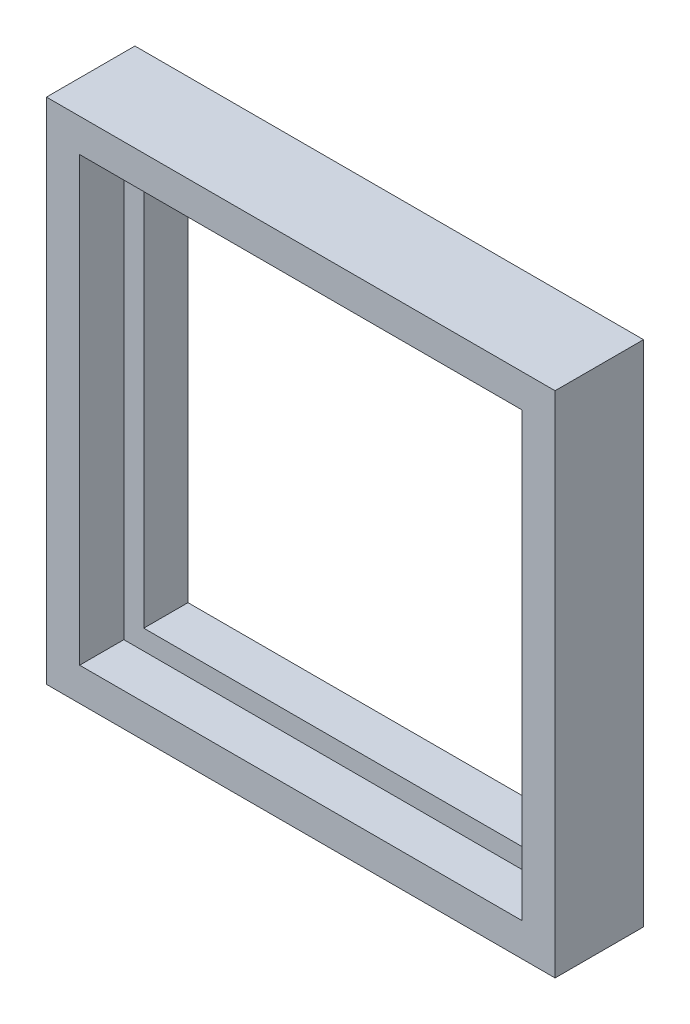
SolidWorks part; units mm, degrees
ref_plane "前视基准面" through (0, 0, 0) normal (0, 0, 1) x (1, 0, 0)
ref_plane "上视基准面" through (0, 0, 0) normal (0, 1, 0) x (1, 0, 0)
ref_plane "右视基准面" through (0, 0, 0) normal (1, 0, 0) x (0, 0, -1)
sketch "草图1" plane through (0, 0, 0) normal (0, 0, 1) x (1, 0, 0)
  line L9 (-5, -5) -> (5, -5)
  line L10 (-5, -5) -> (-5, 5)
  line L11 (-5, 5) -> (5, 5)
  line L12 (5, -5) -> (5, 5)
  line L13 (-5, -5) -> (5, 5) construction
  line L14 (-5, 5) -> (5, -5) construction
  line L15 (-5.75, -5.75) -> (5.75, -5.75)
  line L16 (-5.75, -5.75) -> (-5.75, 5.75)
  line L17 (-5.75, 5.75) -> (5.75, 5.75)
  line L18 (5.75, -5.75) -> (5.75, 5.75)
  line L19 (-5.75, -5.75) -> (5.75, 5.75) construction
  line L20 (-5.75, 5.75) -> (5.75, -5.75) construction
  point P0 (0, 0)
  point P6 (0, 0)
  dimension "D1" = 10
  dimension "D2" = 10
  dimension "D3" = 11.5
  dimension "D4" = 11.5
extrude "凸台-拉伸1" add sketch "草图1" along normal blind 1
sketch "草图2" plane through (0, 0, 0) normal (0, 0, -1) x (-1, 0, 0)
  line L4 (-4.55, -4.55) -> (4.55, -4.55)
  line L5 (4.55, -4.55) -> (4.55, 4.55)
  line L6 (4.55, 4.55) -> (-4.55, 4.55)
  line L7 (-4.55, 4.55) -> (-4.55, -4.55)
  line L8 (-5.75, 5.75) -> (-5.75, -5.75)
  line L9 (-5.75, -5.75) -> (5.75, -5.75)
  line L10 (5.75, -5.75) -> (5.75, 5.75)
  line L11 (5.75, 5.75) -> (-5.75, 5.75)
  line L12 (-5.75, 5.75) -> (-5.75, -5.75)
  line L13 (-5.75, -5.75) -> (5.75, -5.75)
  line L14 (5.75, -5.75) -> (5.75, 5.75)
  line L15 (5.75, 5.75) -> (-5.75, 5.75)
  dimension "D1" = 0
  dimension "D2" = 1.2
extrude "凸台-拉伸2" add sketch "草图2" along normal blind 1
